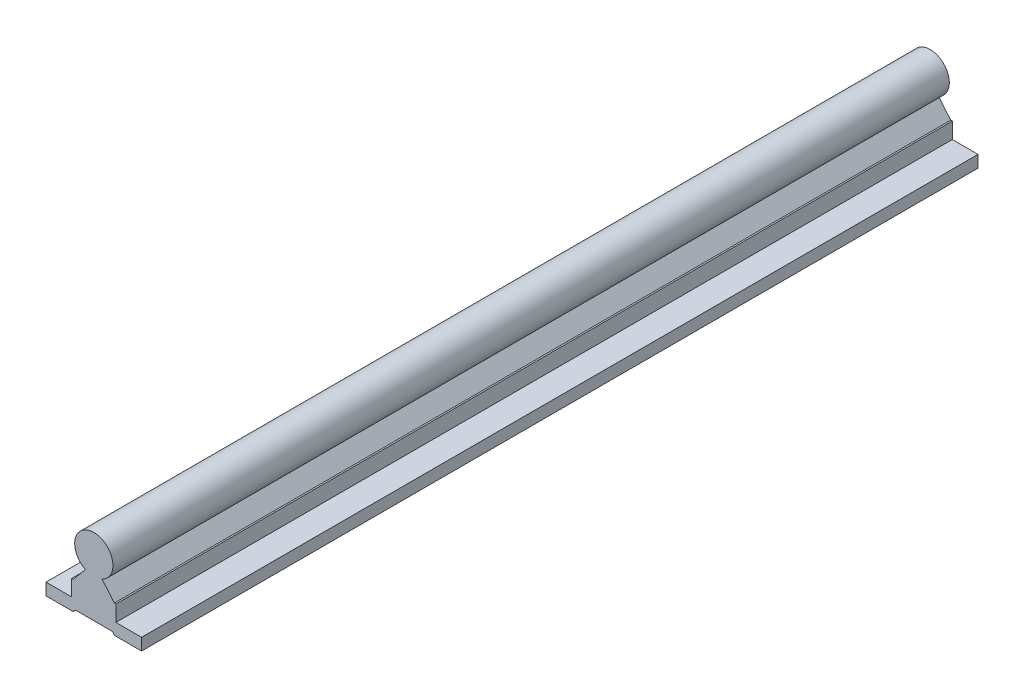
SolidWorks part; units mm, degrees
material "1.0037 (S235JR)"
ref_plane "Płaszczyzna przednia" through (0, 0, 0) normal (0, 0, 1) x (1, 0, 0)
ref_plane "Płaszczyzna górna" through (0, 0, 0) normal (0, 1, 0) x (1, 0, 0)
ref_plane "Płaszczyzna prawa" through (0, 0, 0) normal (1, 0, 0) x (0, 0, -1)
sketch "Szkic1" plane through (0, 0, 0) normal (0, 0, 1) x (1, 0, 0)
  line L0 (0, 0) -> (0, 33) construction
  line L1 (-3.4871, 17.8) -> (-8.6056, 11.7)
  line L2 (-8.6056, 11.7) -> (-9.25, 11.7)
  line L3 (-9.25, 11.7) -> (-9.25, 5)
  line L4 (-9.25, 5) -> (-20, 5)
  line L5 (-20, 5) -> (-20, 0)
  line L6 (-20, 0) -> (-8.6056, 0)
  line L7 (-8.6056, 0) -> (-7.7665, 1)
  line L8 (-7.7665, 1) -> (7.7665, 1)
  line L9 (8.6056, 0) -> (7.7665, 1)
  line L10 (20, 0) -> (8.6056, 0)
  line L11 (20, 5) -> (20, 0)
  line L12 (9.25, 5) -> (20, 5)
  line L13 (9.25, 11.7) -> (9.25, 5)
  line L14 (8.6056, 11.7) -> (9.25, 11.7)
  line L15 (3.4871, 17.8) -> (8.6056, 11.7)
  arc A0 (3.4871, 17.8) -> (-3.4871, 17.8) centre (0, 25) ccw
  point P15 (0, 1)
  dimension "D1" = 1
  dimension "D" = 16
  dimension "W" = 40
  dimension "J" = 18.5
  dimension "O" = 80
  dimension "T" = 5
  dimension "K" = 11.7
  dimension "F" = 17.8
  dimension "H" = 25
extrude "Dodanie-wyciągnięcie1" add sketch "Szkic1" along normal blind 350
sketch "Szkic2" plane through (0, 0, 0) normal (0, -1, 0) x (1, 0, 0)
  line L0 (0, 0) -> (0, 350) construction
  line L1 (-7.7665, 350) -> (7.7665, 350) construction
